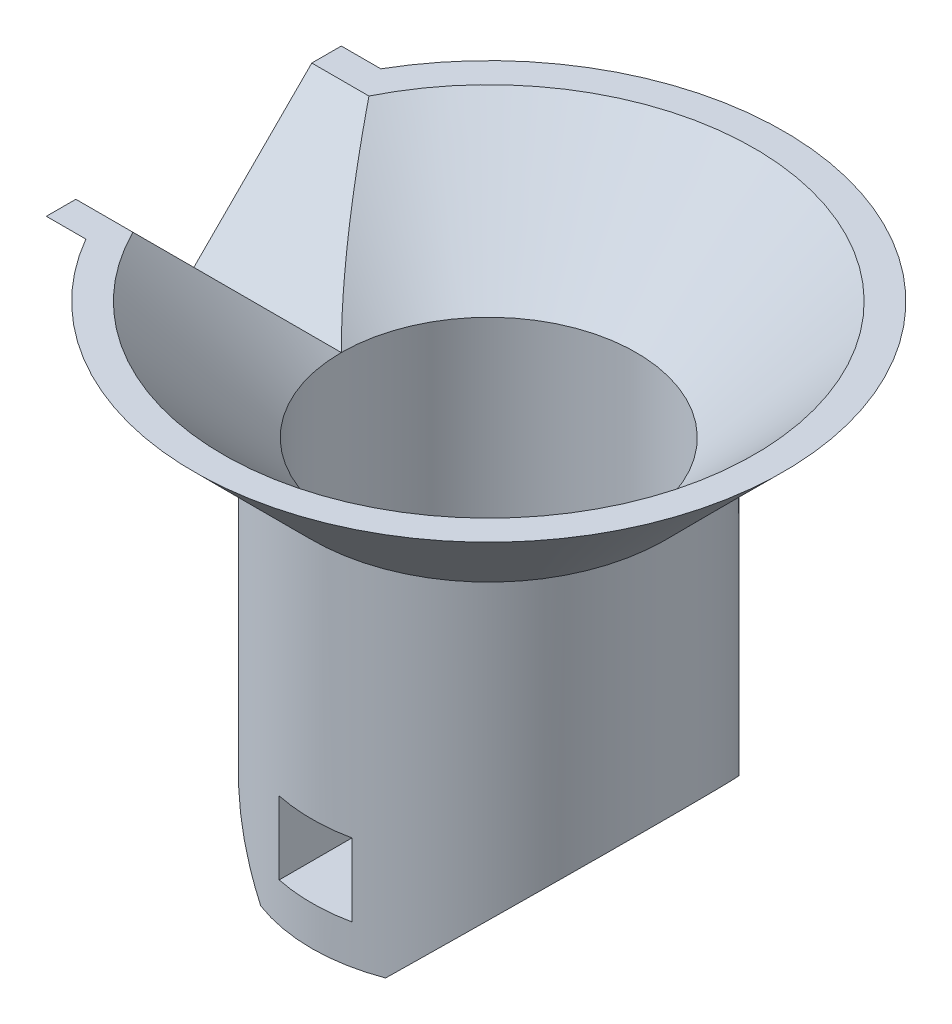
SolidWorks part; units mm, degrees
ref_plane "Front Plane" through (0, 0, 0) normal (0, 0, 1) x (1, 0, 0)
ref_plane "Top Plane" through (0, 0, 0) normal (0, 1, 0) x (1, 0, 0)
ref_plane "Right Plane" through (0, 0, 0) normal (1, 0, 0) x (0, 0, -1)
sketch "Sketch1" plane through (0, 0, 0) normal (0, 1, 0) x (1, 0, 0)
  circle A0 centre (0, 0) radius 9
  dimension "D1" = 18
extrude "Boss-Extrude1" add sketch "Sketch1" along normal blind 18
sketch "Sketch2" plane through (0, 0, 0) normal (0, 0, 1) x (1, 0, 0)
  line L0 (-9, 5.7) -> (-3.175, 0)
  line L1 (-9, 18) -> (-9, 0) construction
  line L2 (-9, 0) -> (9, 0) construction
  line L3 (-3.175, 0) -> (-9, 0)
  line L4 (-9, 0) -> (-9, 5.7)
  line L5 (3.175, 0) -> (9, 5.7)
  line L6 (9, 0) -> (9, 18) construction
  line L7 (9, 5.7) -> (9, 0)
  line L8 (9, 0) -> (3.175, 0)
  line L9 (0, 2) -> (0, 0) construction
  line L10 (-1.85, 5.7) -> (1.85, 5.7)
  line L11 (-1.85, 5.7) -> (-1.85, 2)
  line L12 (-1.85, 2) -> (1.85, 2)
  line L13 (1.85, 5.7) -> (1.85, 2)
  line L14 (-1.85, 2) -> (-5.2189, 2) construction
  dimension "D1" = 3.7
  dimension "D3" = 6.35
  dimension "D4" = 2
extrude "Cut-Extrude1" cut sketch "Sketch2" against normal through all and the other way through all
ref_plane "Plane1" through (0, 6.7, 0) normal (0, -1, 0) x (-1, 0, 0)
sketch "Sketch3" plane through (0, 18, 0) normal (0, 1, 0) x (1, 0, 0)
  circle A0 centre (0, 0) radius 7.5
  circle A1 centre (0, 0) radius 9 construction
  dimension "D1" = 1.5
extrude "Cut-Extrude2" cut sketch "Sketch3" against normal up to surface (11.3 mm away)
sketch "Sketch4" plane through (0, 0, 0) normal (0, 0, 1) x (1, 0, 0)
  line L0 (9, 18) -> (15, 24)
  line L1 (15, 24) -> (13.5, 24)
  line L2 (13.5, 24) -> (7.5, 18)
  line L4 (7.5, 18) -> (9, 18)
  dimension "D1" = 1.5
  dimension "D2" = 135
  dimension "D3" = 6
revolve "Revolve1" add sketch "Sketch4" angle 360 about axis through (0, -14.5132, 0) along (0, 1, 0)
sketch "Sketch5" plane through (0, 0, 0) normal (1, 0, 0) x (0, 0, -1)
  line L0 (0, 18) -> (-6, 24)
  line L1 (9, 18) -> (-9, 18) construction
  line L2 (13.5, 24) -> (-13.5, 24) construction
  line L3 (-6, 24) -> (6, 24)
  line L4 (15, 24) -> (-15, 24) construction
  line L5 (6, 24) -> (0, 18)
extrude "Cut-Extrude3" cut sketch "Sketch5" against normal through all
ref_plane "Plane2" through (-15, 0, 0) normal (1, 0, 0) x (0, 0, -1)
sketch "Sketch6" plane through (-15, 0, 0) normal (1, 0, 0) x (0, 0, -1)
  line L0 (6, 24) -> (0, 18)
  line L1 (0, 18) -> (-6, 24)
  line L2 (-6, 24) -> (-7.5, 24)
  line L3 (13.5, 24) -> (-13.5, 24) construction
  line L4 (-7.5, 24) -> (0, 16.5)
  line L5 (0, 6.7) -> (0, 18) construction
  line L6 (0, 16.5) -> (7.5, 24)
  line L7 (15, 24) -> (-15, 24) construction
  line L8 (7.5, 24) -> (6, 24)
  dimension "D1" = 1.5
extrude "Boss-Extrude2" add sketch "Sketch6" along normal up to next
sketch "Sketch7" plane through (0, 0, 0) normal (0, 0, 1) x (1, 0, 0)
  line L0 (-15, 18) -> (-15, 16.5)
  line L1 (-15, 16.5) -> (-7.5, 9)
  line L3 (7.5, 6.7) -> (7.5, 18)
  line L4 (-7.5, 18) -> (-7.5, 6.7)
  line L5 (-7.5, 18) -> (-15, 18)
  line L6 (-7.5, 18) -> (-7.5, 9)
  dimension "D1" = 45
extrude "Boss-Extrude4" add sketch "Sketch7" along normal mid plane 1.5
